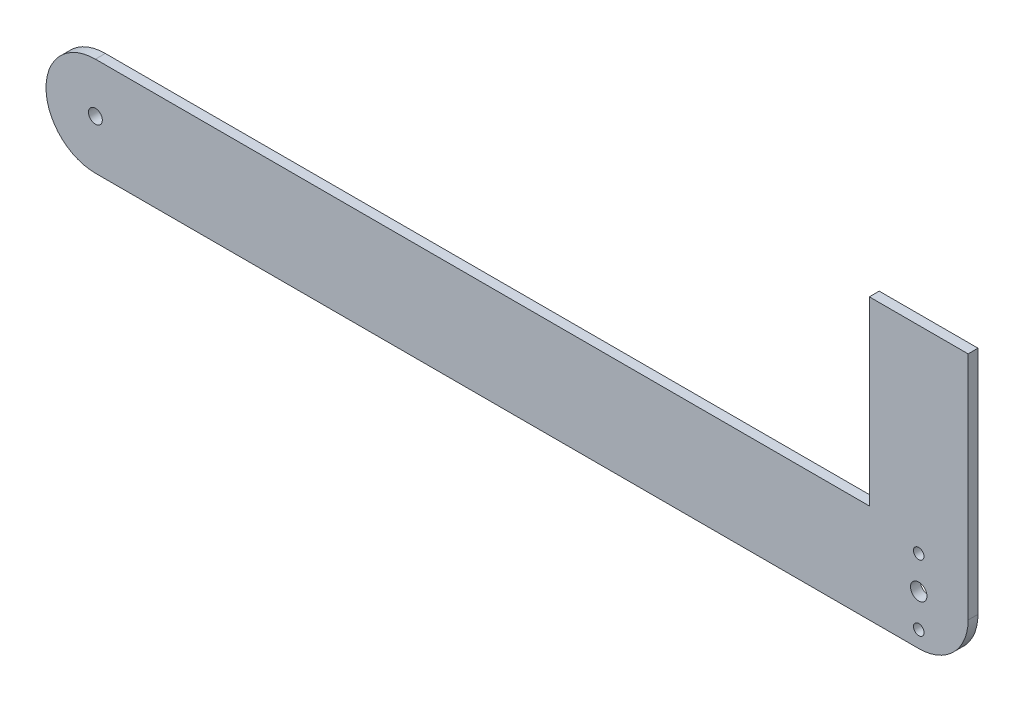
SolidWorks part; units mm, degrees
ref_plane "Plan de face" through (0, 0, 0) normal (0, 0, 1) x (1, 0, 0)
ref_plane "Plan de dessus" through (0, 0, 0) normal (0, 1, 0) x (1, 0, 0)
ref_plane "Plan de droite" through (0, 0, 0) normal (1, 0, 0) x (0, 0, -1)
sketch "Esquisse1" plane through (0, 0, 0) normal (0, 0, 1) x (1, 0, 0)
  line L0 (-125, 15) -> (125, 15)
  line L1 (-125, -15) -> (125, -15)
  line L2 (0, 42.9033) -> (0, -58.9726) construction
  line L3 (111.7564, 0) -> (134.8583, 0) construction
  line L4 (125, 3.4257) -> (125, -4.4088) construction
  arc A0 (125, 15) -> (125, -15) centre (125, 0) cw
  circle A1 centre (125, 0) radius 2.5
  arc A3 (-125, 15) -> (-125, -15) centre (-125, 0) ccw
  circle A4 centre (-125, 0) radius 2.1
  circle A5 centre (125, 10) radius 1.6
  circle A6 centre (125, -10) radius 1.6
  dimension "D2" = 5
  dimension "D5" = 15
  dimension "D1" = 4.2
  dimension "D6" = 3.2
  dimension "D3" = 125
  dimension "D4" = 30
  dimension "D7" = 10
extrude "Boss.-Extru.1" add sketch "Esquisse1" along normal blind 3
sketch "Esquisse2" plane through (0, 0, 3) normal (0, 0, 1) x (1, 0, 0)
  line L0 (109.0858, 0) -> (122.5, 0) construction
  line L1 (110, 70) -> (140, 70)
  line L2 (110, 70) -> (110, 0)
  line L3 (110, 0) -> (122.5, 0)
  line L4 (140, 70) -> (140, 0)
  line L5 (110, 70) -> (140, 0) construction
  line L6 (110, 0) -> (140, 70) construction
  line L7 (125, -6.6904) -> (125, 4.3549) construction
  line L8 (127.5, 0) -> (140, 0) construction
  line L9 (127.5, 0) -> (140, 0)
  arc A0 (127.5, 0) -> (122.5, 0) centre (125, 0) ccw
  circle A1 centre (125, 10) radius 1.6
  point P0 (125, 35)
  dimension "D3" = 2.5
  dimension "D4" = 3.2
  dimension "D1" = 30
  dimension "D2" = 70
extrude "Boss.-Extru.2" add sketch "Esquisse2" against normal blind 3 contours L2 L3 A0 L9 L4 L1
